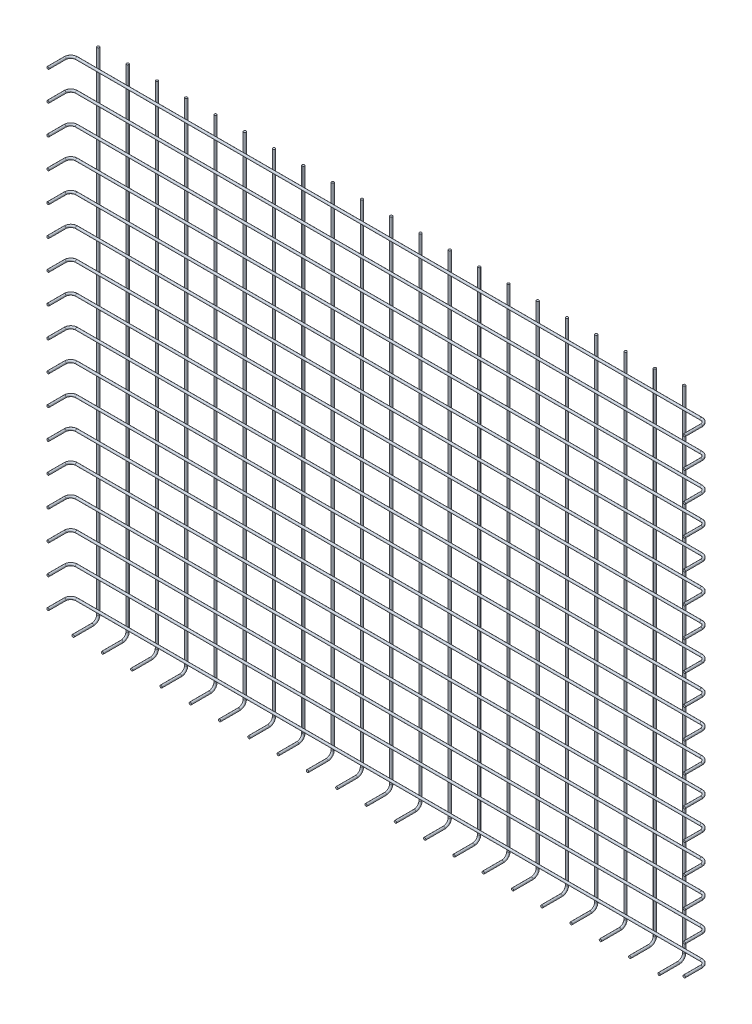
SolidWorks part; units mm, degrees
material "AISI 1020"
ref_plane "Спереди" through (0, 0, 0) normal (0, 0, 1) x (1, 0, 0)
ref_plane "Сверху" through (0, 0, 0) normal (0, 1, 0) x (1, 0, 0)
ref_plane "Справа" through (0, 0, 0) normal (1, 0, 0) x (0, 0, -1)
sketch "Эскиз1" plane through (0, 0, 47) normal (0, 0, 1) x (1, 0, 0)
  line L1 (-545, 0) -> (545, 0) construction
  circle A0 centre (0, 2) radius 2
  point P4 (0, 0)
  dimension "D1" = 4
sketch "Эскиз2" plane through (0, 0, 0) normal (1, 0, 0) x (0, 0, -1)
  line L0 (-47, 2) -> (-14, 2)
  line L1 (-4, 12) -> (-4, 851.0566)
  line L2 (-47, 4) -> (-47, 0) construction
  line L4 (-47, 4) -> (-47, 0) construction
  line L5 (-0.75, 836.0566) -> (-22, 836.0566) construction
  line L6 (-2, 851.0566) -> (-6, 851.0566) construction
  line L7 (-2, -325) -> (-2, 2528.5605) construction
  arc A0 (-14, 2) -> (-4, 12) centre (-14, 12) ccw
  point P5 (-4, 851.0566)
  point P6 (-47, 2)
  dimension "D2" = 10
  dimension "D1" = 15
sweep "По траектории1" add profiles "Эскиз1" path "Эскиз2"
pattern_linear "Линейный массив1" count 11 spacing 50 along (1, 0, 0) of bodies 103
mirror "Зеркальное отражение1" about plane through (0, 0, 0) normal (1, 0, 0) of bodies 113 112 111 110 109 108 107 106 105 104
ref_plane "Плоскость1" through (0, 20, 0) normal (0, 1, 0) x (1, 0, 0)
sketch "Эскиз3" plane through (0, 20, 0) normal (0, 1, 0) x (1, 0, 0)
  line L0 (-543, -47) -> (-543, -18)
  line L1 (-533, -8) -> (533, -8)
  line L2 (543, -18) -> (543, -47)
  line L3 (545, -44) -> (545, 0) construction
  line L4 (-545, 0) -> (-545, -44) construction
  line L5 (-545, -47) -> (545, -47) construction
  circle A0 centre (500, -4) radius 2 construction
  arc A1 (533, -8) -> (543, -18) centre (533, -18) cw
  arc A2 (-543, -18) -> (-533, -8) centre (-533, -18) cw
  point P14 (0, 0)
  point P17 (0, 0)
  dimension "D2" = 4
  dimension "D4" = 10
  dimension "D1" = 2
  dimension "D3" = 2
sketch "Эскиз4" plane through (0, 0, 47) normal (0, 0, 1) x (1, 0, 0)
  circle A0 centre (543, 20) radius 2
  point P1 (0, 0)
  dimension "D1" = 4
sweep "По траектории2" add profiles "Эскиз4" path "Эскиз3"
pattern_linear "Линейный массив2" count 17 spacing 50 along (0, 1, 0) of bodies 124
